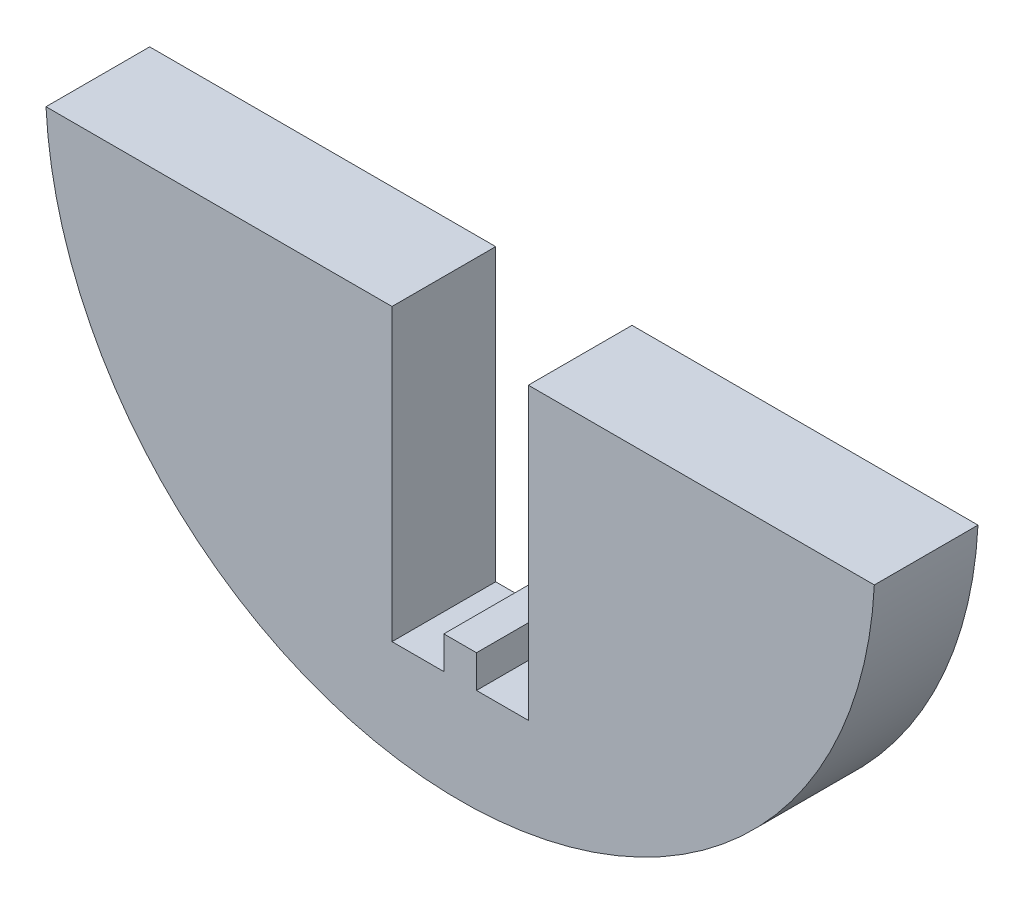
SolidWorks part; units mm, degrees
material "Acrylic (Medium-high impact)"
ref_plane "Front Plane" through (0, 0, 0) normal (1, 0, 0) x (0, 1, 0)
ref_plane "Top Plane" through (0, 0, 0) normal (0, 0, 1) x (0, 1, 0)
ref_plane "Right Plane" through (0, 0, 0) normal (0, 1, 0) x (-1, 0, 0)
sketch3d "3DSketch1"
  line L1 (4.175, -19.05, 0) -> (4.175, -1.27, 0)
  line L7 (-4.175, -1.27, 0) -> (-4.175, -19.05, 0)
  line L8 (0, 0, 0) -> (0, 0, 13.7194) construction
  line L10 (4.175, -19.05, 0) -> (1, -19.05, 0)
  line L11 (1, -19.05, 0) -> (1, -17.05, 0)
  line L12 (1, -17.05, 0) -> (-1, -17.05, 0)
  line L13 (-1, -17.05, 0) -> (-1, -19.05, 0)
  line L14 (-1, -19.05, 0) -> (-4.175, -19.05, 0)
  line L15 (-25.3682, -1.27, 0) -> (-4.175, -1.27, 0)
  line L16 (4.175, -1.27, 0) -> (25.3682, -1.27, 0)
  arc A0 (-25.3682, -1.27, 0) -> (25.3682, -1.27, 0) centre (0, 0, 0) ccw
  point P2 (0, 0, 25.4)
  point P6 (0, 0, 0)
  point P8 (0, 0, 0)
  point P9 (0, 0, 0)
  dimension "D4" = 4.175
  dimension "D5" = 50.8
  dimension "D1" = 2
  dimension "D2" = 2
  dimension "D3" = 3.175
  dimension "D6" = 19.05
  dimension "D7" = 1.27
extrude "Boss-Extrude2" add sketch "3DSketch1" along direction (0, 0, 1) on the side against the normal blind 6.35
equation "\"D4@3DSketch1\"=\"D3@3DSketch1\"+\"D2@3DSketch1\"/2"
